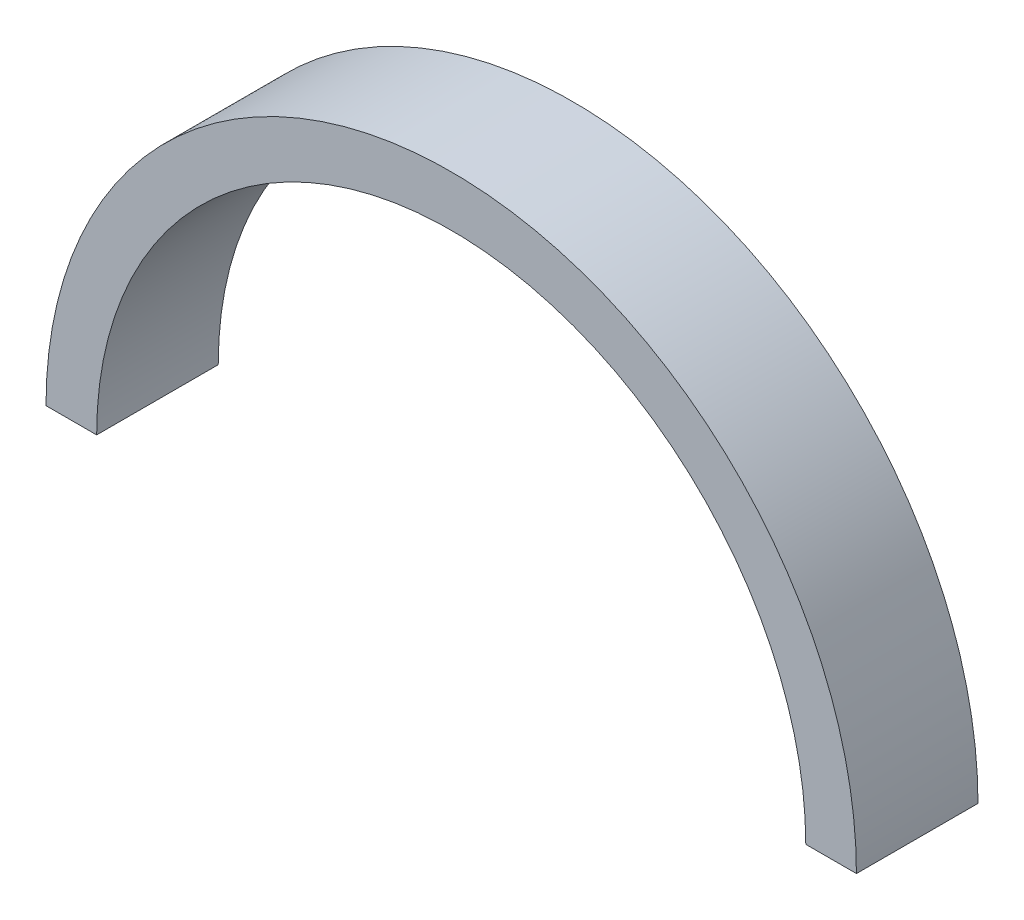
SolidWorks part; units mm, degrees
ref_plane "Front Plane" through (0, 0, 0) normal (0, 0, 1) x (1, 0, 0)
ref_plane "Top Plane" through (0, 0, 0) normal (0, 1, 0) x (1, 0, 0)
ref_plane "Right Plane" through (0, 0, 0) normal (1, 0, 0) x (0, 0, -1)
sketch "Sketch1" plane through (0, 0, 0) normal (0, 0, 1) x (1, 0, 0)
  line L0 (-80, 0) -> (80, 0) construction
  line L1 (80, 180.9422) -> (80, 0) construction
  line L2 (-80, 180.9422) -> (-80, 0) construction
  arc A0 (-80, 0) -> (80, 0) centre (0, 0) cw
  point P4 (0, 0)
  point P7 (0, 0)
  point P8 (0, 0)
  point P9 (0, 0)
  point P10 (0, 0)
  point P11 (0, 0)
  point P12 (0, 0)
  point P13 (0, 0)
  point P14 (0, 0)
  point P15 (0, 0)
extrude "Extrude-Thin1" add sketch "Sketch1" along normal blind 24 thin
